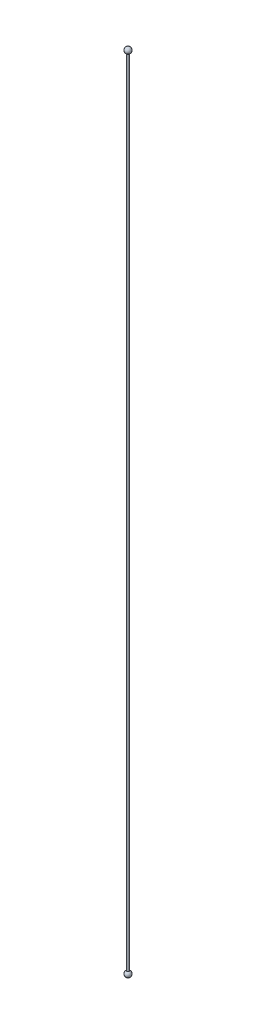
SolidWorks part; units mm, degrees
material "Nylon 6/10"
ref_plane "Front Plane" through (0, 0, 0) normal (0, 0, 1) x (1, 0, 0)
ref_plane "Top Plane" through (0, 0, 0) normal (0, 1, 0) x (1, 0, 0)
ref_plane "Right Plane" through (0, 0, 0) normal (1, 0, 0) x (0, 0, -1)
sketch "Sketch1" plane through (0, 0, 0) normal (0, 0, 1) x (1, 0, 0)
  line L0 (0, -429.8789) -> (0, 21064.0659) construction
  line L1 (0.4, -134.4835) -> (0.4, 134.4835)
  line L2 (0, 136.4) -> (0, -136.4)
  line L3 (-1000, 0) -> (49000, 0) construction
  line L4 (0, 429.8789) -> (0, -21064.0659) construction
  arc A0 (0.4, 134.4835) -> (0, 136.4) centre (0, 135.4) ccw
  arc A1 (0, 134.4) -> (0.4, 134.4835) centre (0, 135.4) ccw construction
  arc A2 (0, -134.4) -> (0.4, -134.4835) centre (0, -135.4) cw construction
  arc A3 (0.4, -134.4835) -> (0, -136.4) centre (0, -135.4) cw
  point P9 (0.4, 0)
  point P17 (0, 0)
  dimension "D1" = 2
  dimension "D2" = 0.4
  dimension "D3" = 134.4
revolve "Revolve1" add sketch "Sketch1" angle 360 about L2
